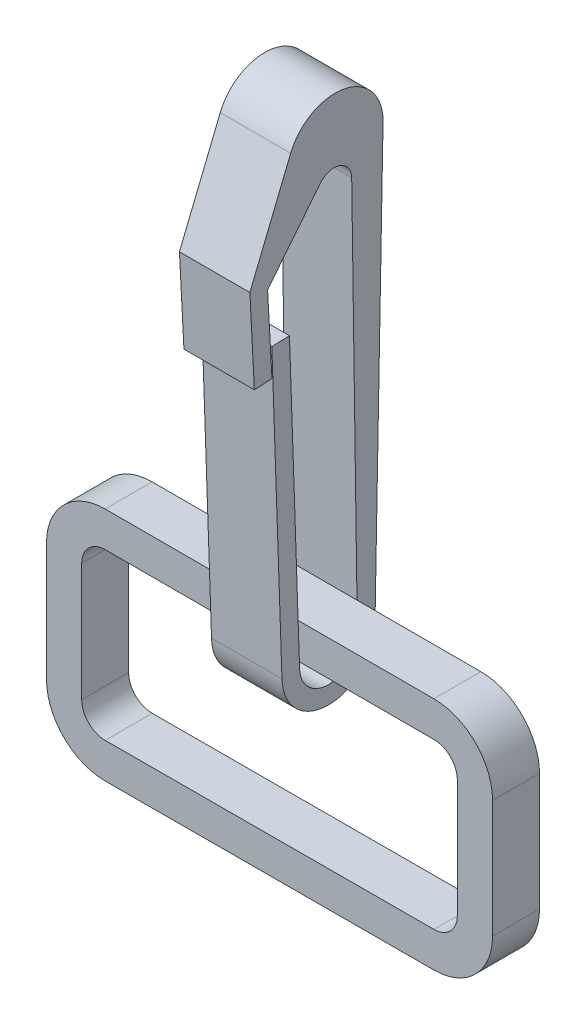
SolidWorks part; units mm, degrees
ref_plane "Plan de face" through (0, 0, 0) normal (0, 0, 1) x (1, 0, 0)
ref_plane "Plan de dessus" through (0, 0, 0) normal (0, 1, 0) x (1, 0, 0)
ref_plane "Plan de droite" through (0, 0, 0) normal (1, 0, 0) x (0, 0, -1)
sketch "Esquisse1" plane through (0, 0, 0) normal (0, 0, 1) x (1, 0, 0)
  line L0 (5.0041, 3.0103) -> (33.004, 3.0679)
  line L1 (5.0103, 0.0103) -> (33.0102, 0.068)
  line L2 (0, 5.0103) -> (0, 15.0782)
  line L3 (5, 20.0782) -> (32.9999, 20.0782)
  line L4 (37.9999, 5.0679) -> (37.9999, 15.0782)
  line L5 (34.9999, 5.0679) -> (34.9999, 15.0782)
  line L6 (5, 17.0782) -> (32.9999, 17.0782)
  line L7 (3, 5.0103) -> (3, 15.0782)
  arc A0 (0, 15.0782) -> (5, 20.0782) centre (5, 15.0782) cw
  arc A1 (32.9999, 20.0782) -> (37.9999, 15.0782) centre (32.9999, 15.0782) cw
  arc A2 (33.0102, 0.068) -> (37.9999, 5.0679) centre (32.9999, 5.0679) ccw
  arc A3 (5.0103, 0.0103) -> (0, 5.0103) centre (5, 5.0103) cw
  arc A4 (33.004, 3.0679) -> (34.9999, 5.0679) centre (32.9999, 5.0679) ccw
  arc A5 (32.9999, 17.0782) -> (34.9999, 15.0782) centre (32.9999, 15.0782) cw
  arc A6 (3, 15.0782) -> (5, 17.0782) centre (5, 15.0782) cw
  arc A7 (5.0041, 3.0103) -> (3, 5.0103) centre (5, 5.0103) cw
  point P8 (37.9999, 20.0782)
  point P11 (37.9999, 0.0782)
  point P14 (0, 0)
  dimension "D3" = 5
  dimension "D1" = 38
  dimension "D2" = 20
  dimension "D4" = 3
extrude "Extrusion1" add sketch "Esquisse1" along normal blind 4
ref_plane "Plan1" through (19, 0, 0) normal (1, 0, 0) x (0, 0, -1)
sketch "Esquisse3" plane through (19, 0, 0) normal (1, 0, 0) x (0, 0, -1)
  line L0 (-4.44, 17.047) -> (-5.3018, 42.0165)
  line L1 (-5.9397, 17.012) -> (-6.8009, 41.9648)
  line L2 (-5.3018, 42.0165) -> (-6.8009, 41.9648)
  line L3 (0.4848, 17.1258) -> (-0.0002, 51.0258)
  line L4 (-2.6708, 51.942) -> (-7.1646, 46.3311)
  line L5 (-6.793, 39.5964) -> (-7.1646, 46.3311)
  line L6 (1.9844, 17.16) -> (2.6696, 53.7481)
  line L7 (-6.793, 39.5964) -> (-8.291, 39.5187)
  line L8 (-8.291, 39.5187) -> (-8.6733, 46.889)
  line L9 (-8.6733, 46.889) -> (-5.1993, 55.4197)
  arc A0 (0.4848, 17.1258) -> (-4.44, 17.047) centre (-1.9773, 17.0695) cw
  arc A1 (1.9844, 17.16) -> (-5.9397, 17.012) centre (-1.9773, 17.0695) cw
  arc A2 (-2.6708, 51.942) -> (-0.0002, 51.0258) centre (-1.5, 51.0044) cw
  arc A4 (2.6696, 53.7481) -> (-5.1993, 55.4197) centre (-1.4147, 53.8784) ccw
  dimension "D2" = 1.5
  dimension "D1" = 1.5
extrude "Extrusion6" add sketch "Esquisse3" along normal blind 3 and the other way blind 3
